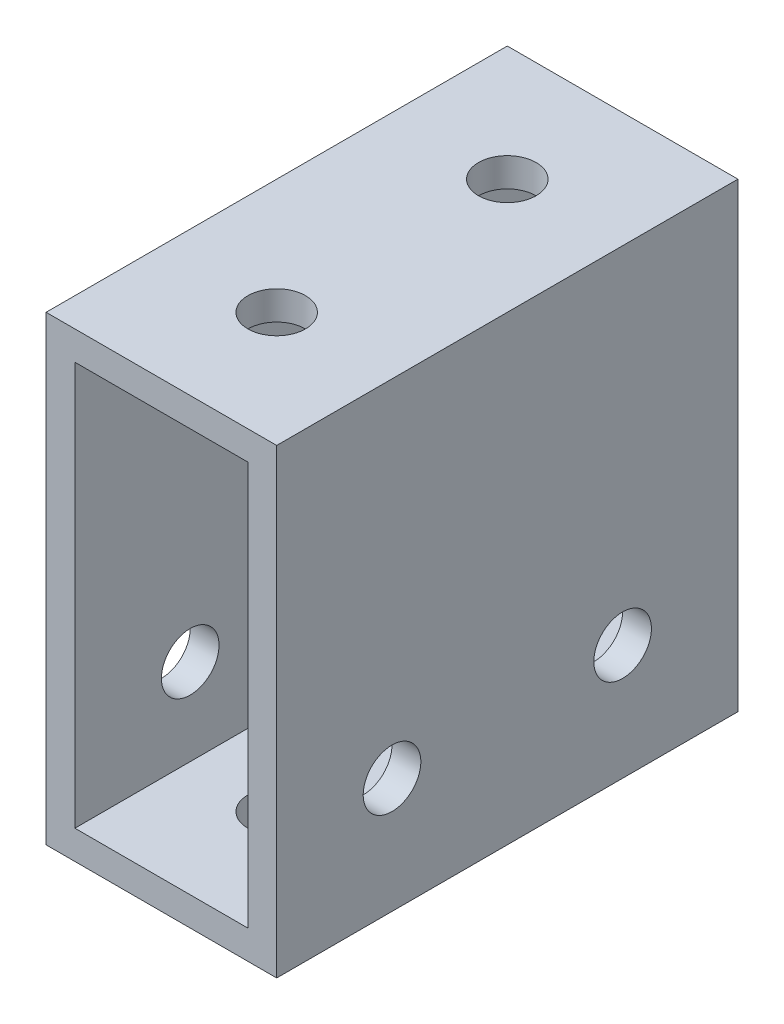
SolidWorks part; units mm, degrees
ref_plane "Front Plane" through (0, 0, 0) normal (0, 0, 1) x (1, 0, 0)
ref_plane "Top Plane" through (0, 0, 0) normal (0, 1, 0) x (1, 0, 0)
ref_plane "Right Plane" through (0, 0, 0) normal (1, 0, 0) x (0, 0, -1)
sketch "Sketch1" plane through (0, 0, 0) normal (0, 0, 1) x (1, 0, 0)
  line L1 (0, 0) -> (25.4, 0)
  line L2 (0, 0) -> (0, 50.8)
  line L3 (0, 50.8) -> (25.4, 50.8)
  line L4 (25.4, 0) -> (25.4, 50.8)
  line L5 (3.175, 47.625) -> (22.225, 47.625)
  line L6 (3.175, 47.625) -> (3.175, 3.175)
  line L7 (3.175, 3.175) -> (22.225, 3.175)
  line L8 (22.225, 47.625) -> (22.225, 3.175)
  dimension "D1" = 50.8
  dimension "D2" = 25.4
  dimension "D3" = 3.175
  dimension "D4" = 3.175
  dimension "D5" = 3.175
  dimension "D6" = 3.175
extrude "Boss-Extrude1" add sketch "Sketch1" along normal blind 50.8
sketch "Sketch2" plane through (0, 0, 0) normal (0, -1, 0) x (1, 0, 0)
  line L0 (25.4, 50.8) -> (25.4, 0) construction
  line L1 (0, 0) -> (25.4, 0) construction
  circle A0 centre (12.7, 38.1) radius 3.175
  circle A1 centre (12.7, 12.7) radius 3.175
  dimension "D1" = 6.35
  dimension "D4" = 6.35
  dimension "D2" = 12.7
  dimension "D3" = 12.7
  dimension "D5" = 12.7
  dimension "D6" = 38.1
extrude "Cut-Extrude1" cut sketch "Sketch2" against normal blind 50.8
sketch "Sketch3" plane through (0, 0, 0) normal (-1, 0, 0) x (0, 0, 1)
  line L0 (50.8, 0) -> (0, 0) construction
  line L1 (50.8, 50.8) -> (50.8, 0) construction
  circle A0 centre (38.1, 12.7) radius 3.175
  circle A1 centre (12.7, 12.7) radius 3.175
  dimension "D1" = 6.35
  dimension "D2" = 12.7
  dimension "D3" = 38.1
  dimension "D4" = 12.7
  dimension "D5" = 12.7
extrude "Cut-Extrude2" cut sketch "Sketch3" against normal blind 50.8
